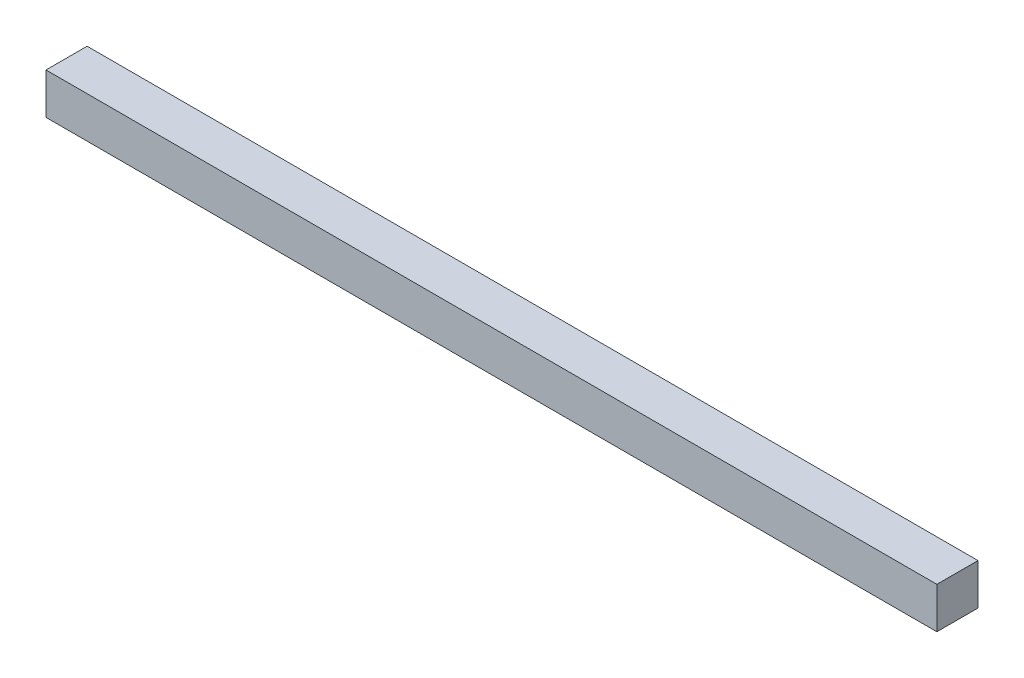
SolidWorks part; units mm, degrees
ref_plane "正面" through (0, 0, 0) normal (0, 0, 1) x (1, 0, 0)
ref_plane "平面" through (0, 0, 0) normal (0, 1, 0) x (1, 0, 0)
ref_plane "右側面" through (0, 0, 0) normal (1, 0, 0) x (0, 0, -1)
sketch "ｽｹｯﾁ2" plane through (0, 0, 0) normal (0, 0, 1) x (1, 0, 0)
  line L1 (0, 0) -> (260, 0)
  line L2 (0, 0) -> (0, 12)
  line L3 (0, 12) -> (260, 12)
  line L4 (260, 0) -> (260, 12)
  dimension "D1" = 260
  dimension "D2" = 12
extrude "ﾎﾞｽ - 押し出し1" add sketch "ｽｹｯﾁ2" along normal blind 12
